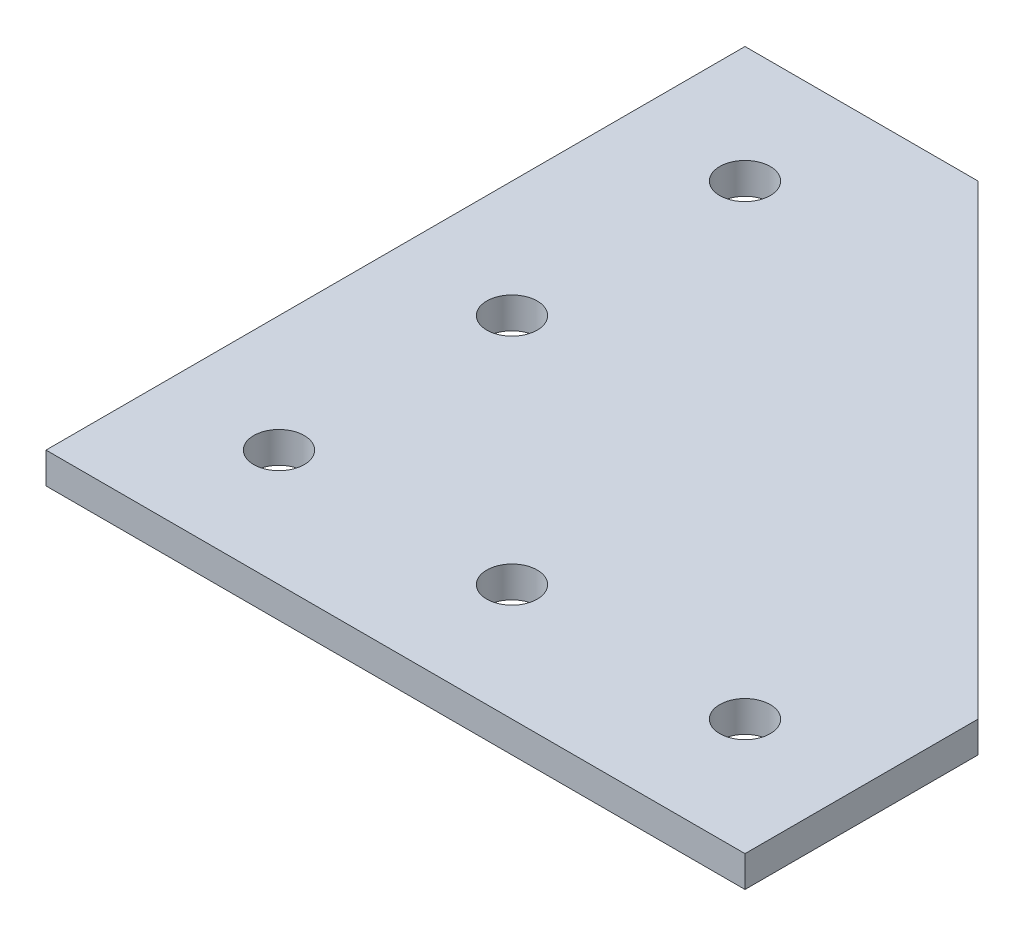
SolidWorks part; units mm, degrees
ref_plane "Front Plane" through (0, 0, 0) normal (0, 0, 1) x (1, 0, 0)
ref_plane "Top Plane" through (0, 0, 0) normal (0, 1, 0) x (1, 0, 0)
ref_plane "Right Plane" through (0, 0, 0) normal (1, 0, 0) x (0, 0, -1)
sketch "Sketch1" plane through (0, 0, 0) normal (0, 1, 0) x (1, 0, 0)
  line L0 (0, 0) -> (90, 0)
  line L1 (90, 0) -> (90, 30)
  line L2 (90, 30) -> (30, 90)
  line L3 (30, 90) -> (0, 90)
  line L4 (0, 90) -> (0, 0)
  dimension "D1" = 90
  dimension "D2" = 90
  dimension "D3" = 30
  dimension "D4" = 30
extrude "Boss-Extrude1" add sketch "Sketch1" along normal blind 4
sketch "Sketch2" plane through (0, 4, 0) normal (0, 1, 0) x (1, 0, 0)
  line L0 (0, 0) -> (90, 0) construction
  line L1 (0, 90) -> (0, 0) construction
  circle A0 centre (15, 15) radius 3.25
  circle A1 centre (45, 15) radius 3.25
  circle A2 centre (75, 15) radius 3.25
  circle A3 centre (15, 45) radius 3.25
  circle A4 centre (15, 75) radius 3.25
  dimension "D1" = 6.5
  dimension "D2" = 15
  dimension "15" = 15
  dimension "D5" = 30
  dimension "D6" = 30
  dimension "D3" = 3
  dimension "D4" = 3
extrude "Cut-Extrude1" cut sketch "Sketch2" against normal through all
